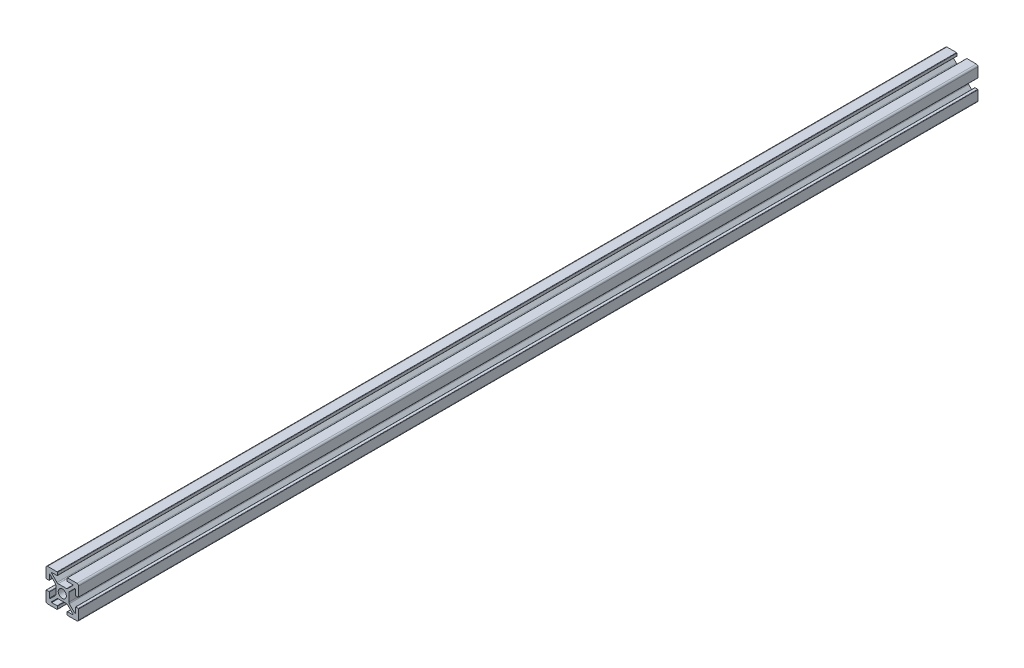
SolidWorks part; units mm, degrees
ref_plane "Front Plane" through (0, 0, 0) normal (0, 0, 1) x (1, 0, 0)
ref_plane "Top Plane" through (0, 0, 0) normal (0, 1, 0) x (1, 0, 0)
ref_plane "Right Plane" through (0, 0, 0) normal (1, 0, 0) x (0, 0, -1)
sketch "Sketch1" plane through (0, 0, 0) normal (0, 0, 1) x (1, 0, 0)
  line L0 (0.2, 13) -> (1.8, 13)
  line L1 (13.2, 0) -> (19, 0)
  line L2 (0, 13.2) -> (0, 19)
  line L3 (1, 20) -> (6.8, 20)
  line L4 (20, 1) -> (20, 6.8)
  line L5 (2, 13.2) -> (2, 16.5)
  line L6 (2, 16.5) -> (2.4393, 16.5)
  line L7 (2.4393, 16.5) -> (5.7071, 13.2322)
  line L8 (6, 12.5251) -> (6, 7.4749)
  line L11 (7.4749, 14) -> (10, 14)
  line L12 (3.5, 17.5607) -> (6.7678, 14.2929)
  line L13 (3.5, 18) -> (3.5, 17.5607)
  line L14 (6.8, 18) -> (3.5, 18)
  line L15 (6.8, 20) -> (1, 20)
  line L16 (7, 19.8) -> (7, 18.2)
  line L17 (19.8, 7) -> (18.2, 7)
  line L18 (20, 6.8) -> (20, 1)
  line L19 (18, 6.8) -> (18, 3.5)
  line L20 (18, 3.5) -> (17.5607, 3.5)
  line L21 (17.5607, 3.5) -> (14.2929, 6.7678)
  line L22 (14, 7.4749) -> (14, 12.5251)
  line L23 (12.5251, 6) -> (10, 6)
  line L24 (16.5, 2.4393) -> (13.2322, 5.7071)
  line L25 (16.5, 2) -> (16.5, 2.4393)
  line L26 (13.2, 2) -> (16.5, 2)
  line L27 (13.2, 0) -> (19, 0)
  line L28 (13, 0.2) -> (13, 1.8)
  line L30 (13, 19.8) -> (13, 18.2)
  line L31 (13.2, 20) -> (19, 20)
  line L32 (13.2, 18) -> (16.5, 18)
  line L33 (16.5, 18) -> (16.5, 17.5607)
  line L34 (16.5, 17.5607) -> (13.2322, 14.2929)
  line L35 (12.5251, 14) -> (10, 14)
  line L36 (17.5607, 16.5) -> (14.2929, 13.2322)
  line L37 (18, 16.5) -> (17.5607, 16.5)
  line L38 (18, 13.2) -> (18, 16.5)
  line L39 (20, 13.2) -> (20, 19)
  line L40 (19.8, 13) -> (18.2, 13)
  line L41 (7, 0.2) -> (7, 1.8)
  line L42 (6.8, 0) -> (1, 0)
  line L43 (6.8, 2) -> (3.5, 2)
  line L44 (3.5, 2) -> (3.5, 2.4393)
  line L45 (3.5, 2.4393) -> (6.7678, 5.7071)
  line L46 (7.4749, 6) -> (10, 6)
  line L47 (2.4393, 3.5) -> (5.7071, 6.7678)
  line L48 (2, 3.5) -> (2.4393, 3.5)
  line L49 (2, 6.8) -> (2, 3.5)
  line L50 (20, 19) -> (20, 13.2)
  line L51 (1, 0) -> (6.8, 0)
  line L52 (0, 6.8) -> (0, 1)
  line L53 (13.2, 20) -> (19, 20)
  line L54 (0.2, 7) -> (1.8, 7)
  arc A0 (20, 1) -> (19, 0) centre (19, 1) cw
  arc A1 (1, 0) -> (0, 1) centre (1, 1) cw
  arc A2 (0, 19) -> (1, 20) centre (1, 19) cw
  arc A3 (20, 19) -> (19, 20) centre (19, 19) ccw
  arc A4 (14.2929, 6.7678) -> (14, 7.4749) centre (15, 7.4749) cw
  arc A5 (12.5251, 6) -> (13.2322, 5.7071) centre (12.5251, 5) cw
  arc A6 (6.7678, 5.7071) -> (7.4749, 6) centre (7.4749, 5) cw
  arc A7 (5.7071, 6.7678) -> (6, 7.4749) centre (5, 7.4749) ccw
  arc A8 (14.2929, 13.2322) -> (14, 12.5251) centre (15, 12.5251) ccw
  arc A9 (13.2322, 14.2929) -> (12.5251, 14) centre (12.5251, 15) cw
  arc A10 (6, 12.5251) -> (5.7071, 13.2322) centre (5, 12.5251) ccw
  arc A11 (7.4749, 14) -> (6.7678, 14.2929) centre (7.4749, 15) cw
  arc A12 (0, 6.8) -> (0.2, 7) centre (0.2, 6.8) cw
  arc A13 (2, 6.8) -> (1.8, 7) centre (1.8, 6.8) ccw
  arc A14 (7, 1.8) -> (6.8, 2) centre (6.8, 1.8) ccw
  arc A15 (7, 0.2) -> (6.8, 0) centre (6.8, 0.2) cw
  arc A16 (13.2, 0) -> (13, 0.2) centre (13.2, 0.2) cw
  arc A17 (13.2, 2) -> (13, 1.8) centre (13.2, 1.8) ccw
  arc A18 (18.2, 7) -> (18, 6.8) centre (18.2, 6.8) ccw
  arc A19 (19.8, 7) -> (20, 6.8) centre (19.8, 6.8) cw
  arc A20 (20, 13.2) -> (19.8, 13) centre (19.8, 13.2) cw
  arc A21 (18, 13.2) -> (18.2, 13) centre (18.2, 13.2) ccw
  arc A22 (13, 19.8) -> (13.2, 20) centre (13.2, 19.8) cw
  arc A23 (13, 18.2) -> (13.2, 18) centre (13.2, 18.2) ccw
  arc A24 (6.8, 18) -> (7, 18.2) centre (6.8, 18.2) ccw
  arc A25 (7, 19.8) -> (6.8, 20) centre (6.8, 19.8) ccw
  arc A26 (1.8, 13) -> (2, 13.2) centre (1.8, 13.2) ccw
  arc A27 (0.2, 13) -> (0, 13.2) centre (0.2, 13.2) cw
  circle A28 centre (10, 10) radius 2.5
  point P19 (2, 13)
  dimension "D1" = 1
  dimension "D4" = 1
  dimension "D5" = 0.2
  dimension "D6" = 0.2
  dimension "D7" = 5
  dimension "D2" = 7
  dimension "D3" = 2
  dimension "D9" = 3.5
extrude "Boss-Extrude1" add sketch "Sketch1" along normal blind 552 contours A27 L0 A26 L5 L6 L7 A10 L8 A7 L47 L48 L49 A13 L54 A12 L52 A1 L42 A15 L41 A14 L43 L44 L45 A6 L46 L23 A5 L24 L25 L26 A17 L28 A16 L1 A0 L4 A19 L17 A18 L19 L20 L21 A4 L22 A8 L36 L37 L38 A21 L40
